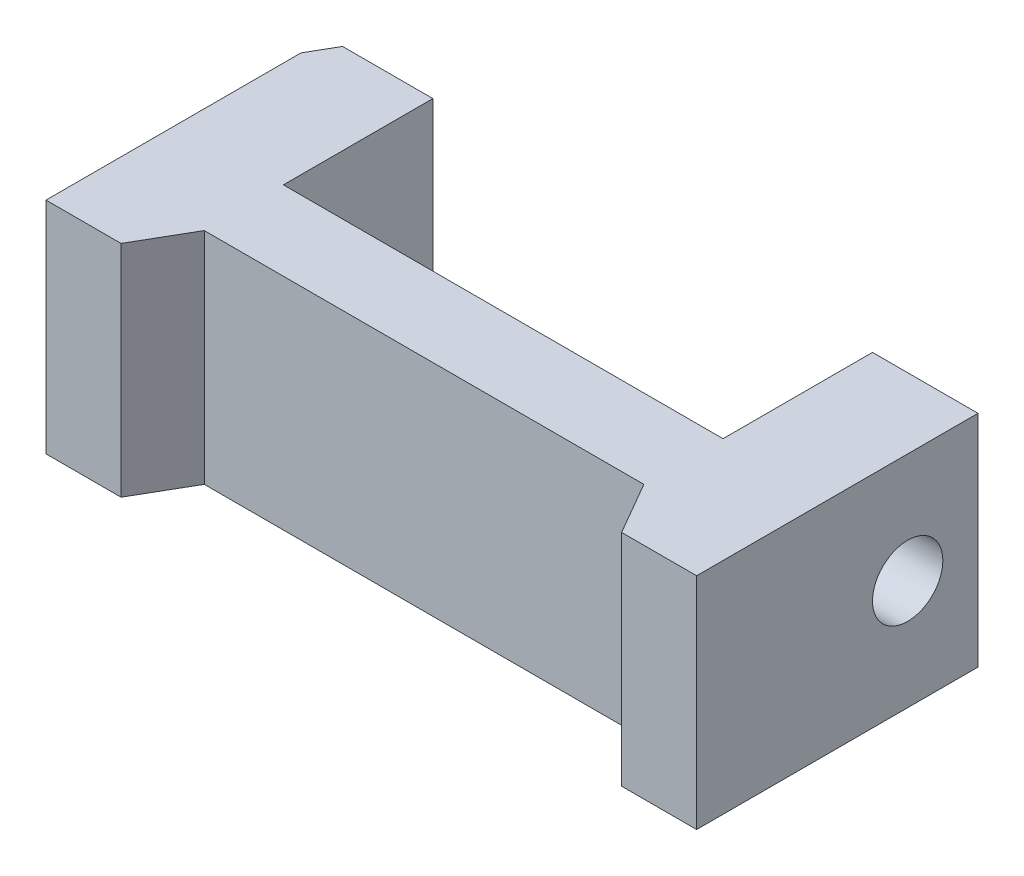
SolidWorks part; units mm, degrees
ref_plane "Front Plane" through (0, 0, 0) normal (0, 0, 1) x (1, 0, 0)
ref_plane "Top Plane" through (0, 0, 0) normal (0, 1, 0) x (1, 0, 0)
ref_plane "Right Plane" through (0, 0, 0) normal (1, 0, 0) x (0, 0, -1)
sketch "Sketch1" plane through (0, 0, 0) normal (0, 1, 0) x (1, 0, 0)
  line L0 (0, 0) -> (0, 33652.228) construction
  line L1 (0, 0) -> (-33652.228, 0) construction
  line L2 (-34.9953, 4) -> (-34.9953, 33)
  line L3 (-34.9953, 33) -> (-33.2632, 36)
  line L4 (-33.2632, 36) -> (-22.9953, 36)
  line L5 (-22.9953, 36) -> (-22.9953, 19)
  line L6 (-22.9953, 19) -> (27.0047, 19)
  line L7 (27.0047, 19) -> (27.0047, 36)
  line L8 (27.0047, 36) -> (39.0047, 36)
  line L9 (39.0047, 36) -> (39.0047, 4)
  line L10 (39.0047, 4) -> (30.4688, 4)
  line L11 (30.4688, 4) -> (27.0047, 10)
  line L12 (27.0047, 10) -> (-22.9953, 10)
  line L13 (-22.9953, 10) -> (-26.4594, 4)
  line L14 (-26.4594, 4) -> (-34.9953, 4)
  point P8 (-28.754, 20.0479)
  point P19 (0, 0)
  point P20 (0, 0)
  point P21 (-19.9326, -4.2647)
  point P22 (-16.6333, 1.4876)
  point P23 (-18.9914, 20.95)
  point P24 (-35.7192, 36)
  point P25 (-35.1831, 4)
  point P26 (-31.9665, 10)
  point P27 (27.0047, 10)
  dimension "D1" = 50
  dimension "D2" = 32
  dimension "D3" = 12
  dimension "D4" = 12
  dimension "D5" = 6
  dimension "D6" = 9
  dimension "D7" = 30
  dimension "D8" = 3
  dimension "D9" = 30
  dimension "D10" = 10
extrude "Boss-Extrude1" add sketch "Sketch1" along normal blind 25
hole_wizard "Ø8.0mm Dowel Hole2" positions "Sketch4" profile "Sketch5" hole size "Ø8.0" standard "ISO"
sketch "Sketch4" plane through (39.0047, 0, 0) normal (1, 0, 0) x (0, 0, -1)
  line L0 (4, 25) -> (36, 25) construction
  line L1 (36, 25) -> (36, 0) construction
  point P0 (28, 12.5)
  dimension "D1" = 12.5
  dimension "D2" = 8
sketch "Sketch5" plane through (39.0047, 12.5, -28) normal (0, 1, 0) x (0, 0, -1)
  line L0 (0, 0) -> (0, 12)
  line L1 (0, 12) -> (4, 12)
  line L2 (4, 12) -> (4, 0)
  line L5 (4, 0) -> (0, 0)
  line L11 (0, -6.35) -> (0, 107.95) construction
  dimension "Thru Hole Dia." = 8
  dimension "Thru Hole Depth" = 12
